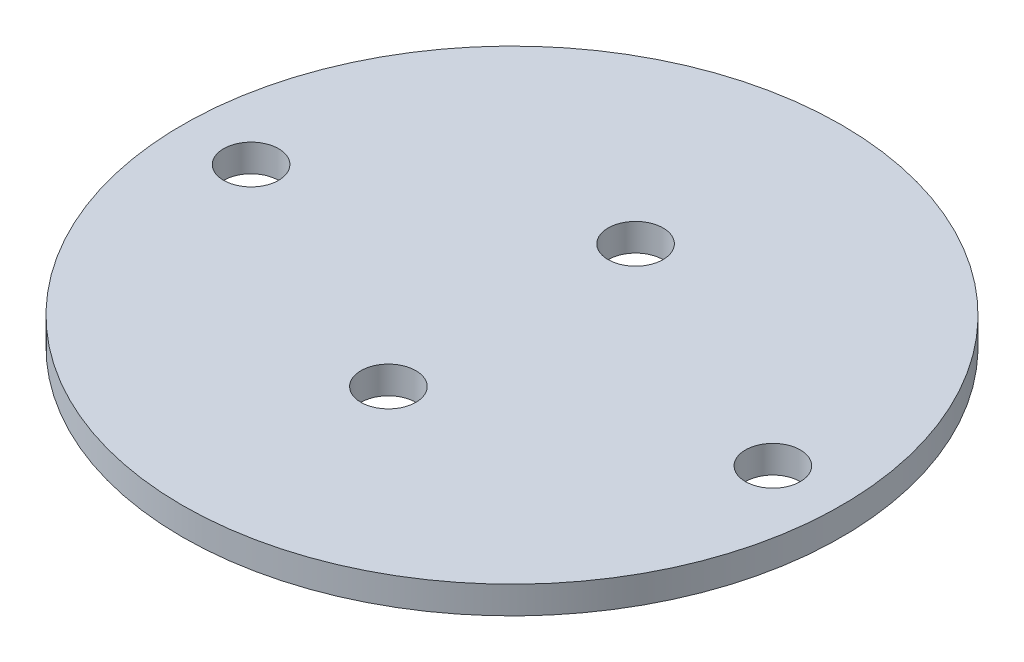
SolidWorks part; units mm, degrees
ref_plane "Front Plane" through (0, 0, 0) normal (0, 0, 1) x (1, 0, 0)
ref_plane "Top Plane" through (0, 0, 0) normal (0, 1, 0) x (1, 0, 0)
ref_plane "Right Plane" through (0, 0, 0) normal (1, 0, 0) x (0, 0, -1)
sketch "Sketch1" plane through (0, 0, 0) normal (0, 1, 0) x (1, 0, 0)
  line L0 (-24.5585, 0) -> (32.4415, 0) construction
  line L1 (3.9415, 0) -> (3.9415, 13.5)
  line L2 (3.9415, 0) -> (3.9415, -13.5)
  circle A0 centre (3.9415, 0) radius 36
  circle A1 centre (32.4415, 0) radius 3
  circle A2 centre (-24.5585, 0) radius 3
  circle A3 centre (3.9415, 13.5) radius 3
  circle A4 centre (3.9415, -13.5) radius 3
  circle A5 centre (-24.5585, 0) radius 6.25 construction
  circle A6 centre (3.9415, 13.5) radius 12.5 construction
  circle A7 centre (3.9415, -13.5) radius 12.5 construction
  circle A8 centre (32.4415, 0) radius 6.25 construction
  point P11 (3.9415, 0)
  dimension "D1" = 72
  dimension "D3" = 6
  dimension "D4" = 13.5
  dimension "D5" = 6
  dimension "D6" = 12.5
  dimension "D7" = 25
  dimension "D2" = 57
extrude "Boss-Extrude1" add sketch "Sketch1" against normal blind 3
